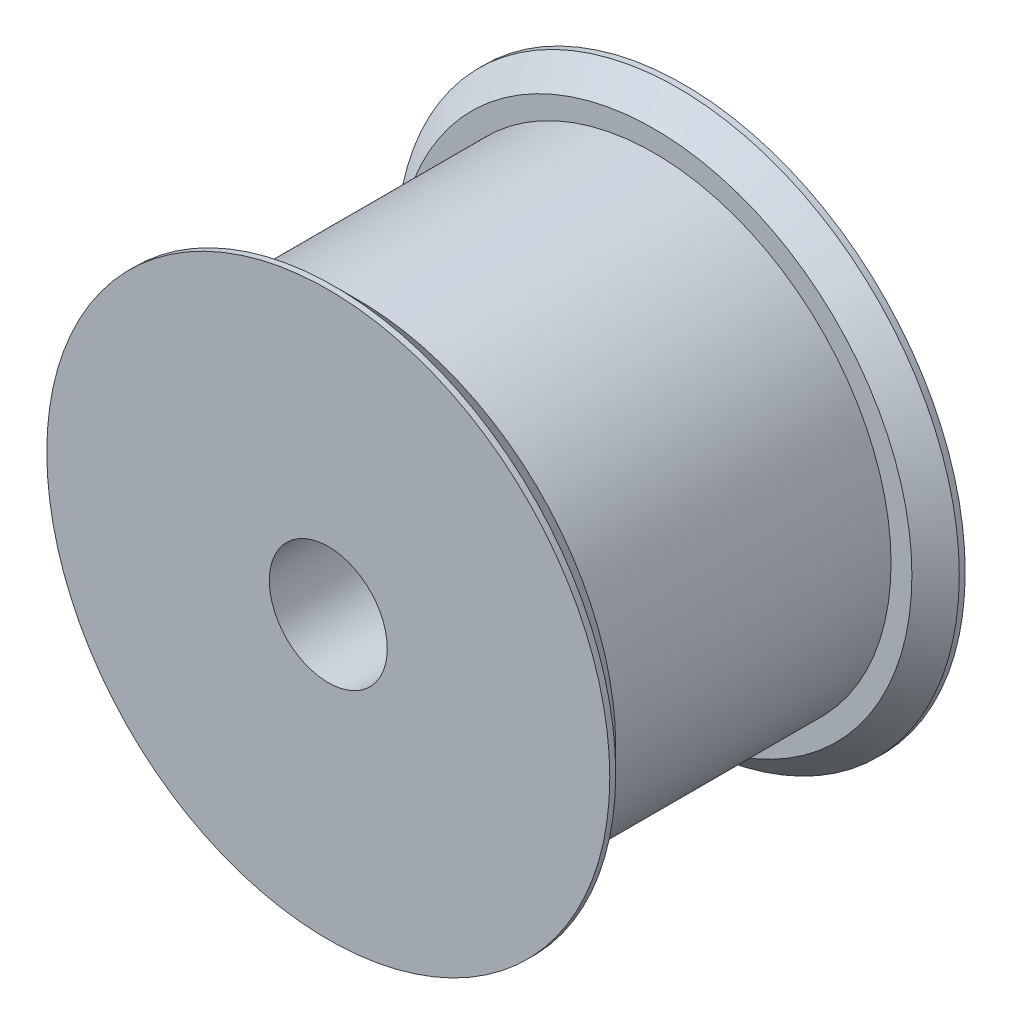
SolidWorks part; units mm, degrees
material "ABS"
ref_plane "Alzado" through (0, 0, 0) normal (0, 0, 1) x (1, 0, 0)
ref_plane "Planta" through (0, 0, 0) normal (0, 1, 0) x (1, 0, 0)
ref_plane "Vista lateral" through (0, 0, 0) normal (1, 0, 0) x (0, 0, -1)
sketch "Croquis1" plane through (0, 0, 0) normal (0, 0, 1) x (1, 0, 0)
  circle A0 centre (0, 0) radius 20
  dimension "D1" = 40
extrude "Saliente-Extruir1" add sketch "Croquis1" along normal mid plane 25
sketch "Croquis2" plane through (0, 0, 12.5) normal (0, 0, 1) x (1, 0, 0)
  circle A0 centre (0, 0) radius 23.7606
extrude "Saliente-Extruir2" add sketch "Croquis2" along normal blind 2.5
chamfer "Chaflán1" distance 2 angle 45 1 edges at (23.7606, 0, 12.5)
mirror "Simetría1" about plane through (0, 0, 0) normal (0, 0, 1) of "Saliente-Extruir2", "Chaflán1"
sketch "Croquis3" plane through (0, 0, 15) normal (0, 0, 1) x (1, 0, 0)
  circle A0 centre (0, 0) radius 4.9786
extrude "Cortar-Extruir1" cut sketch "Croquis3" against normal through all
